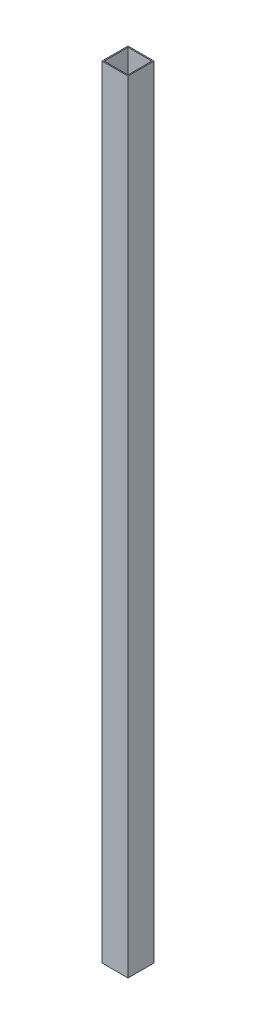
SolidWorks part; units mm, degrees
ref_plane "Front Plane" through (0, 0, 0) normal (0, 0, 1) x (1, 0, 0)
ref_plane "Top Plane" through (0, 0, 0) normal (0, 1, 0) x (1, 0, 0)
ref_plane "Right Plane" through (0, 0, 0) normal (1, 0, 0) x (0, 0, -1)
sketch "Sketch1" plane through (0, 0, 0) normal (0, 1, 0) x (1, 0, 0)
  line L1 (12.5, -12.5) -> (-12.5, -12.5)
  line L2 (12.5, -12.5) -> (12.5, 12.5)
  line L3 (12.5, 12.5) -> (-12.5, 12.5)
  line L4 (-12.5, -12.5) -> (-12.5, 12.5)
  line L5 (12.5, -12.5) -> (-12.5, 12.5) construction
  line L6 (12.5, 12.5) -> (-12.5, -12.5) construction
  line L7 (11.5, -11.5) -> (-11.5, -11.5)
  line L8 (11.5, -11.5) -> (11.5, 11.5)
  line L9 (11.5, 11.5) -> (-11.5, 11.5)
  line L10 (-11.5, -11.5) -> (-11.5, 11.5)
  line L11 (11.5, -11.5) -> (-11.5, 11.5) construction
  line L12 (11.5, 11.5) -> (-11.5, -11.5) construction
  point P0 (0, 0)
  point P6 (0, 0)
  dimension "D1" = 25
  dimension "D2" = 1
extrude "Boss-Extrude1" add sketch "Sketch1" along normal blind 750
